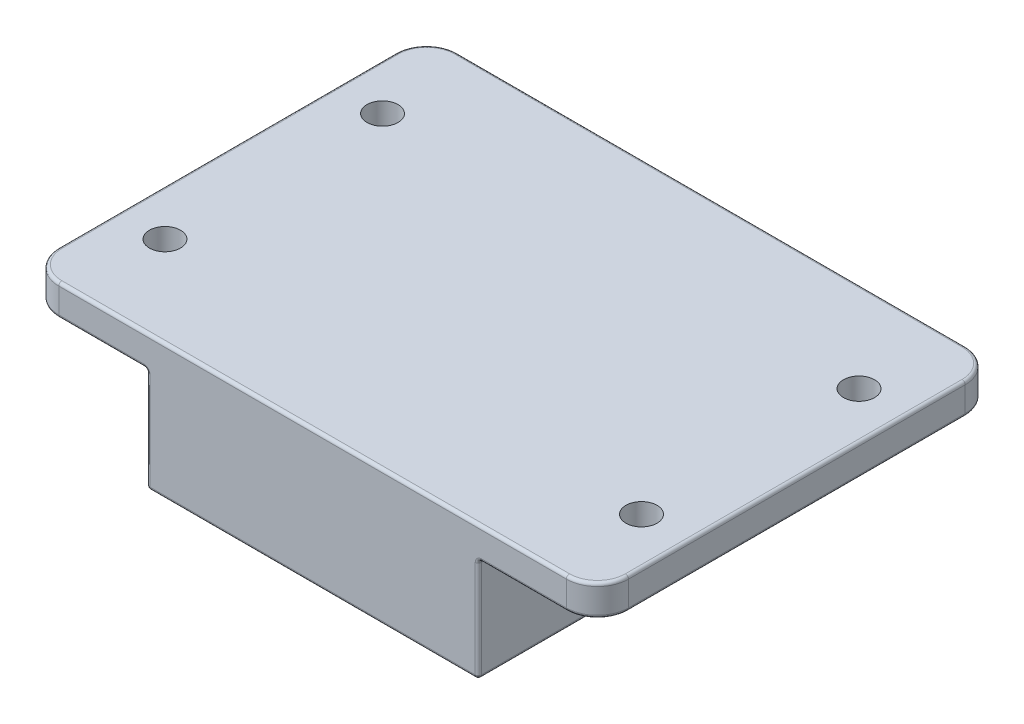
SolidWorks part; units mm, degrees
ref_plane "前视基准面" through (0, 0, 0) normal (0, 0, 1) x (1, 0, 0)
ref_plane "上视基准面" through (0, 0, 0) normal (0, 1, 0) x (1, 0, 0)
ref_plane "右视基准面" through (0, 0, 0) normal (1, 0, 0) x (0, 0, -1)
sketch "草图1" plane through (0, 0, 0) normal (0, 1, 0) x (1, 0, 0)
  line L1 (-27.5, -19.25) -> (27.5, -19.25)
  line L2 (-27.5, -19.25) -> (-27.5, 19.25)
  line L3 (-27.5, 19.25) -> (27.5, 19.25)
  line L4 (27.5, -19.25) -> (27.5, 19.25)
  line L5 (-27.5, -19.25) -> (27.5, 19.25) construction
  line L6 (-27.5, 19.25) -> (27.5, -19.25) construction
  point P0 (0, 0)
  dimension "D1" = 55
  dimension "D2" = 38.5
extrude "凸台-拉伸1" add sketch "草图1" along normal blind 3
fillet "圆角1" radius 3 4 edges at (27.5, 1.5, -19.25) (27.5, 1.5, 19.25) (-27.5, 1.5, 19.25) (-27.5, 1.5, -19.25)
sketch "草图2" plane through (0, 0, 0) normal (0, -1, 0) x (1, 0, 0)
  line L0 (0, 22.3416) -> (0, -23.148) construction
  line L1 (-30.3692, 0) -> (30.5158, 0) construction
  circle A0 centre (-23, 10.5) radius 1.5
  circle A1 centre (23, 10.5) radius 1.5
  circle A2 centre (23, -10.5) radius 1.5
  circle A3 centre (-23, -10.5) radius 1.5
  point P9 (-22.6715, 15.6703)
  point P10 (-24.2844, 3.8672)
  dimension "D1" = 3
  dimension "D2" = 46
  dimension "D3" = 21
extrude "切除-拉伸1" cut sketch "草图2" against normal blind 3
sketch "草图3" plane through (0, 0, 0) normal (0, -1, 0) x (1, 0, 0)
  line L0 (0, 22.2683) -> (0, -23.5512) construction
  line L1 (-16, 19.25) -> (-16, -19.25)
  line L2 (-24.5, 19.25) -> (24.5, 19.25) construction
  line L3 (24.5, -19.25) -> (-24.5, -19.25) construction
  line L4 (16, 19.25) -> (16, -19.25)
  line L5 (-16, 19.25) -> (16, 19.25)
  line L6 (-16, -19.25) -> (16, -19.25)
  dimension "D1" = 16
extrude "凸台-拉伸2" add sketch "草图3" along normal blind 10
sketch "草图4" plane through (0, 0, -19.25) normal (0, 0, -1) x (-1, 0, 0)
  line L0 (-10.3552, -4.978) -> (-4.7661, -4.978) construction
  line L1 (-10.3552, -3.1772) -> (-4.7661, -3.1772)
  line L2 (-10.3552, -6.7788) -> (-4.7661, -6.7788)
  line L3 (3.5038, -3.252) -> (8.2188, -3.252)
  line L4 (8.2188, -3.252) -> (9.1951, -4.2283)
  line L5 (9.1951, -4.2283) -> (9.739, -5.7701)
  line L6 (9.739, -5.7701) -> (1.9836, -5.7701)
  line L7 (5.8613, -5.7701) -> (5.8613, -1.8926) construction
  line L8 (2.5275, -4.2283) -> (1.9836, -5.7701)
  line L9 (3.5038, -3.252) -> (2.5275, -4.2283)
  arc A0 (-10.3552, -3.1772) -> (-10.3552, -6.7788) centre (-10.3552, -4.978) ccw
  arc A1 (-4.7661, -6.7788) -> (-4.7661, -3.1772) centre (-4.7661, -4.978) ccw
  point P2 (-7.5607, -4.978)
extrude "切除-拉伸2" cut sketch "草图4" against normal blind 10
fillet "圆角2" radius 0.3 2 edges at (-9.739, -5.7701, -14.25) (-1.9836, -5.7701, -14.25)
fillet "圆角3" radius 0.3 40 edges at (-20.25, 0, 19.25) (-26.6213, 0, 18.3713) (-27.5, 0, 0) (-26.6213, 0, -18.3713) (20.25, 0, 19.25) (26.6213, 0, 18.3713) (27.5, 0, 0) (26.6213, 0, -18.3713) (26.6213, 3, -18.3713) (27.5, 3, 0) (26.6213, 3, 18.3713) (0, 3, 19.25) (-26.6213, 3, 18.3713) (-27.5, 3, 0) (-26.6213, 3, -18.3713) (-20.25, 0, -19.25) (20.25, 0, -19.25) (0, 3, -19.25) (-2.1626, -5.6434, -19.25) (-5.8613, -5.7701, -19.25) (-9.56, -5.6434, -19.25) (-9.3966, -4.7993, -19.25) (-8.707, -3.7402, -19.25) (-5.8613, -3.252, -19.25) (-3.0156, -3.7402, -19.25) (-2.326, -4.7993, -19.25) (2.9653, -4.978, -19.25) (7.5607, -3.1772, -19.25) (12.156, -4.978, -19.25) (7.5607, -6.7788, -19.25) (16, -5, -19.25) (16, -5, 19.25) (16, 0, 0) (-16, -5, 19.25) (-16, -5, -19.25) (-16, 0, 0) (16, -10, 0) (0, -10, -19.25) (-16, -10, 0) (0, -10, 19.25)
